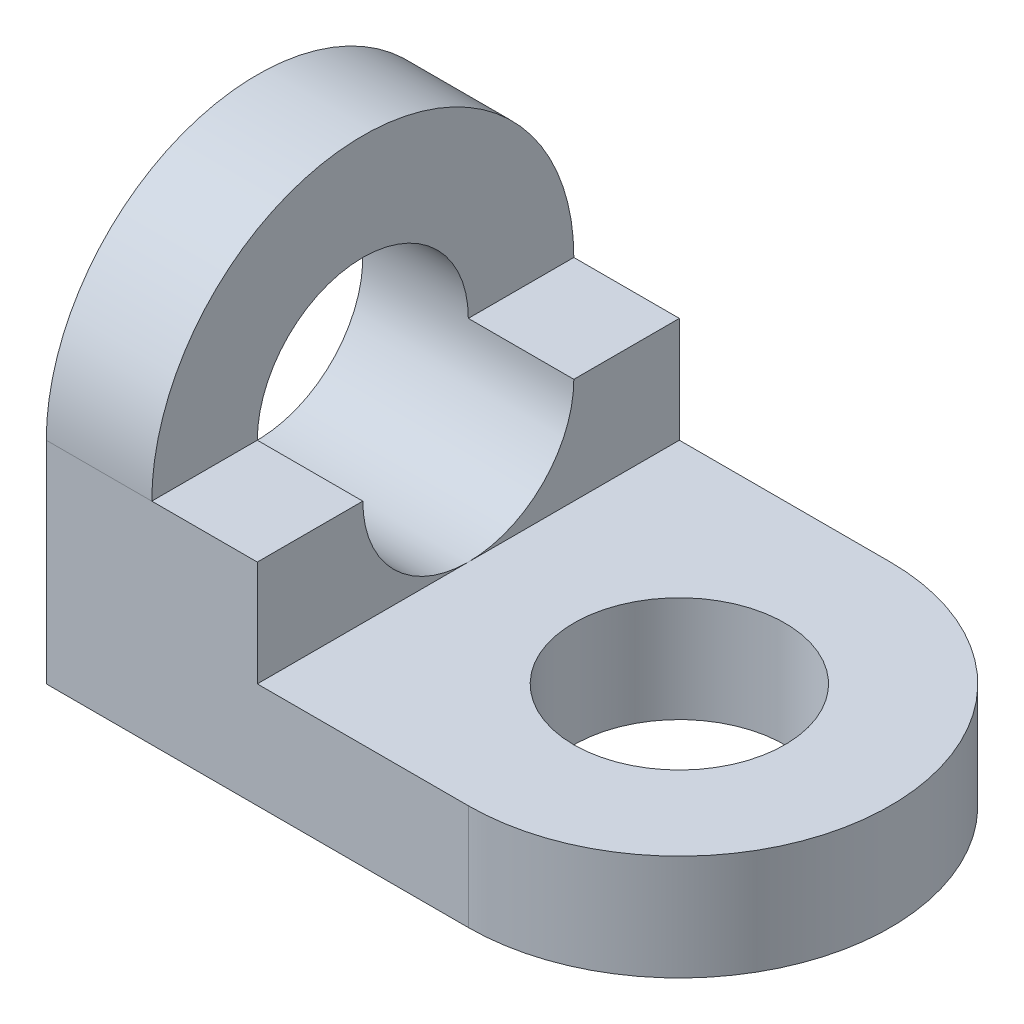
SolidWorks part; units mm, degrees
ref_plane "前基準面" through (0, 0, 0) normal (0, 0, 1) x (1, 0, 0)
ref_plane "上基準面" through (0, 0, 0) normal (0, 1, 0) x (1, 0, 0)
ref_plane "右基準面" through (0, 0, 0) normal (1, 0, 0) x (0, 0, -1)
sketch "草圖1" plane through (0, 0, 0) normal (0, 1, 0) x (1, 0, 0)
  line L0 (0, 10) -> (-20, 10)
  line L1 (-20, 10) -> (-20, -10)
  line L2 (-20, -10) -> (0, -10)
  circle A0 centre (0, 0) radius 5
  arc A1 (0, -10) -> (0, 10) centre (0, 0) ccw
  dimension "D1" = 10
  dimension "D2" = 10
  dimension "D3" = 20
  dimension "D4" = 20
extrude "填料-伸長1" add sketch "草圖1" along normal blind 5
sketch "草圖2" plane through (-20, 0, 0) normal (-1, 0, 0) x (0, 0, 1)
  line L0 (-10, 0) -> (10, 0) construction
  line L1 (-10, 0) -> (10, 0)
  line L2 (-10, 0) -> (-10, 10)
  line L3 (10, 10) -> (10, 0)
  arc A0 (-10, 10) -> (10, 10) centre (0, 10) cw
  circle A1 centre (0, 10) radius 5
  dimension "D1" = 10
  dimension "D3" = 10
  dimension "D2" = 10
extrude "填料-伸長2" add sketch "草圖2" against normal blind 5
sketch "草圖3" plane through (-15, 0, 0) normal (1, 0, 0) x (0, 0, -1)
  line L1 (-10, 5) -> (0, 5) construction
  line L2 (0, 5) -> (10, 5) construction
  line L8 (10, 10) -> (10, 5) construction
  line L9 (0, 5) -> (10, 5)
  line L10 (-10, 5) -> (0, 5)
  line L11 (10, 10) -> (10, 5)
  line L12 (-10, 5) -> (-10, 10) construction
  line L13 (-10, 5) -> (-10, 10)
  line L14 (-10, 10) -> (-5, 10)
  line L15 (5, 10) -> (10, 10)
  circle A0 centre (0, 10) radius 5 construction
  arc A4 (-5, 10) -> (5, 10) centre (0, 10) ccw
  line M1 (-10, 10) -> (-10, 5)
  line M2 (-10, 5) -> (0, 5)
  circle M3 centre (0, 10) radius 5
  line M4 (0, 5) -> (10, 5)
  line M5 (10, 5) -> (10, 10)
extrude "填料-伸長3" add sketch "草圖3" along normal blind 5 contours L14 M1 M2 M3 | L15 M3 M4 M5
